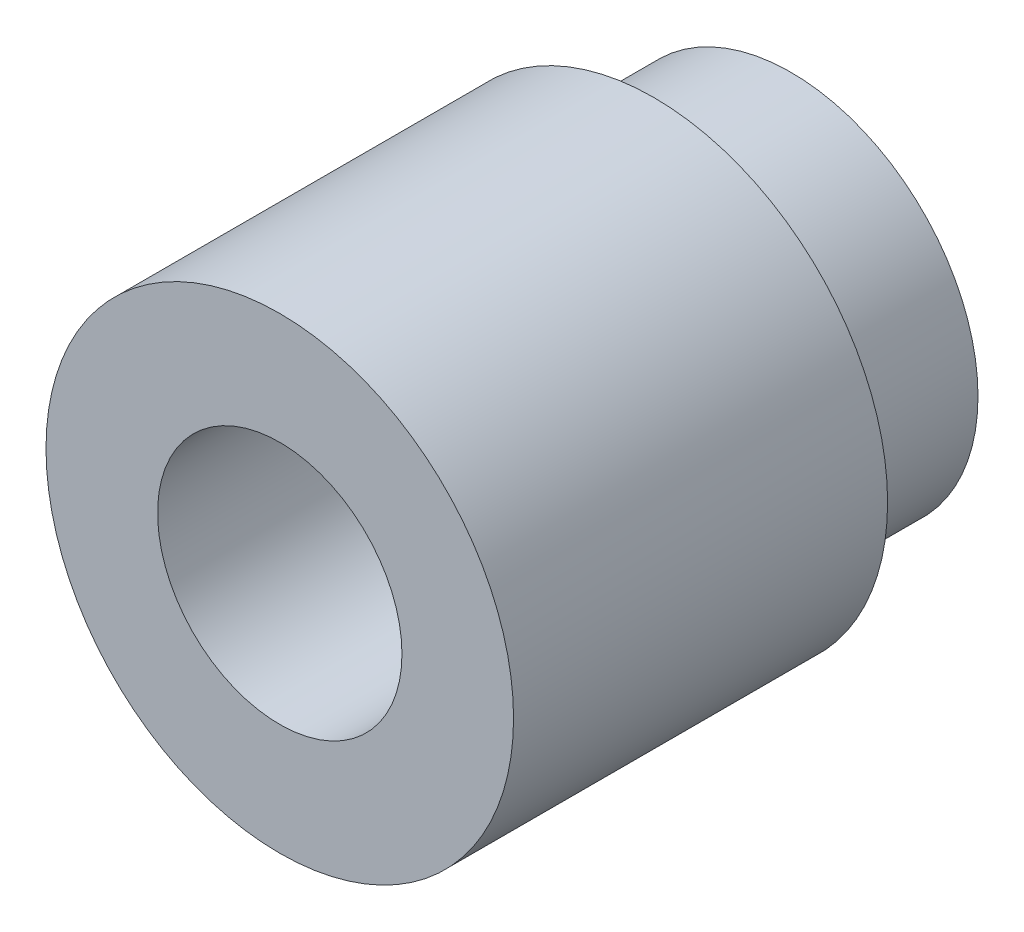
SolidWorks part; units mm, degrees
material "6061-T6 (SS)"
ref_plane "Front Plane" through (0, 0, 0) normal (0, 0, 1) x (1, 0, 0)
ref_plane "Top Plane" through (0, 0, 0) normal (0, 1, 0) x (1, 0, 0)
ref_plane "Right Plane" through (0, 0, 0) normal (1, 0, 0) x (0, 0, -1)
sketch "Sketch1" plane through (0, 0, 0) normal (1, 0, 0) x (0, 0, -1)
  line L0 (-10.8779, 0) -> (13.59, 0) construction
  line L1 (0, 2.4892) -> (10.414, 2.4892)
  line L2 (10.414, 2.4892) -> (10.414, 3.81)
  line L3 (10.414, 3.81) -> (7.62, 3.81)
  line L4 (7.62, 3.81) -> (7.62, 4.7625)
  line L5 (7.62, 4.7625) -> (0, 4.7625)
  line L6 (0, 4.7625) -> (0, 2.4892)
  dimension "D1" = 2.794
  dimension "D2" = 7.62
  dimension "D3" = 4.9784
  dimension "D4" = 9.525
  dimension "D5" = 7.62
revolve "Revolve1" add sketch "Sketch1" angle 360 about L0
